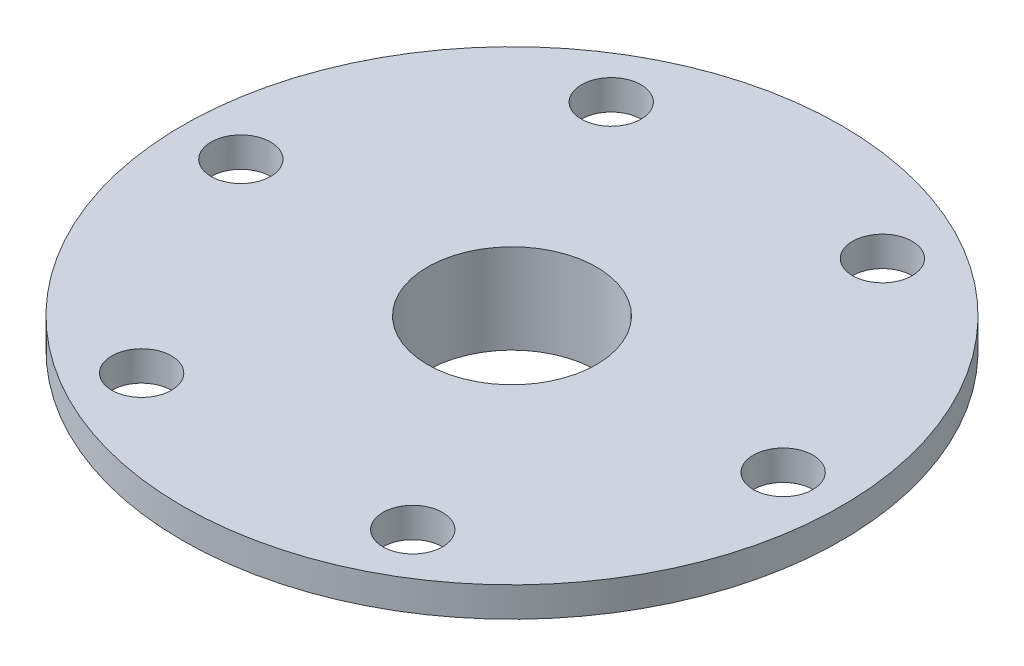
SolidWorks part; units mm, degrees
material "1060 Alloy"
ref_plane "Front Plane" through (0, 0, 0) normal (0, 0, 1) x (1, 0, 0)
ref_plane "Top Plane" through (0, 0, 0) normal (0, 1, 0) x (1, 0, 0)
ref_plane "Right Plane" through (0, 0, 0) normal (1, 0, 0) x (0, 0, -1)
sketch "Sketch4" plane through (0, 0, 0) normal (0, 0, 1) x (1, 0, 0)
  line L0 (0, 27.2792) -> (0, -44.2975) construction
  line L1 (-8.5, 0) -> (-33.1437, 0)
  line L2 (-33.1437, 0) -> (-33.1438, -3)
  line L3 (-33.1438, -3) -> (-12.25, -3)
  line L4 (-12.25, -3) -> (-12.25, -9)
  line L5 (-12.25, -9) -> (-8.5, -9)
  line L6 (-8.5, -9) -> (-8.5, 0)
  line L7 (0, 15) -> (-42.0375, 15) construction
  line L8 (0, 20) -> (-12.5, 20) construction
  line L9 (-12.5, 20) -> (-42.0375, 15) construction
  line L10 (-27.2687, 17.5) -> (-27.2688, 15) construction
  dimension "D2" = 3
  dimension "D3" = 8.5
  dimension "D4" = 12.25
  dimension "D5" = 6
  dimension "D6" = 15
  dimension "D7" = 42.0375
  dimension "D8" = 12.5
  dimension "D9" = 5
  dimension "D1" = 5.875
revolve "Revolve1" add sketch "Sketch4" angle 360 about L0
sketch "Sketch5" plane through (0, 0, 0) normal (0, 1, 0) x (1, 0, 0)
  line L0 (-12.5, 0) -> (-42.0375, 0) construction
  circle A0 centre (0, 0) radius 27.2688 construction
  circle A1 centre (-27.2688, 0) radius 3
  circle A2 centre (-13.6344, 23.6154) radius 3
  circle A3 centre (13.6344, 23.6154) radius 3
  circle A4 centre (27.2688, 0) radius 3
  circle A5 centre (13.6344, -23.6154) radius 3
  circle A6 centre (-13.6344, -23.6154) radius 3
  circle A7 centre (0, 0) radius 12.5 construction
  circle A9 centre (0, 0) radius 42.0375 construction
  point P17 (0, 0)
  point P19 (0, 0)
  dimension "D2" = 6
  dimension "D3" = 25
  dimension "D4" = 84.075
  dimension "D1" = 6
extrude "Cut-Extrude1" cut sketch "Sketch5" against normal through all
equation "\"Stator_OD\"= 68'No Tolerance given"
equation "\"A\"=18.34 'taken off spec sheet for 06808 (A)"
equation "\"Rotor_ID\"= 34'No Tolerance Given"
equation "\"back_bearing_Thickness\"= 8'randomish, thinnest off mcmaster"
equation "\"back_bearing_OD\"= 25'currently non-sense"
equation "\"Stator_Gap\"= 0.0375'+- 0.0125 (From 1.3.3.1 Kollmorgen manual)"
equation "\"Back_mount_hole\"= 1.75'To be tapped to M2 (USE LOCKTITE)"
equation "\"facePlate_Mount_Hole\"= 5.75'To be tapped to M6"
equation "\"final_shaftD\"= 8'NEMA 23 shaft diameter. Should fit with harmonic?"
equation "\"final_shaftL\"= 50'random length. Idk"
equation "\"back_bearing_ID\"= 15'Random number"
equation "\"back_bearing_IDOD\"= 18'Random number, OD of the inner bearing ring"
equation "\"rotor_shaftD\"= \"Rotor_ID\" - (0.0185)*2'+-0.0065 (from manual)"
equation "\"front_bearing_ID\"= 12'random"
equation "\"front_bearing_OD\"= 20'random"
equation "\"front_bearing_IDOD\"= 14'random"
equation "\"front_bearing_Thickness\"= 5'randomish, thinnest off mcmaster"
equation "\"rotor_thickness\"= 2.4'measured off CAD"
equation "\"rotor_height\"= 14.76'+-0.08 taken off spec sheet for 06808 (C)"
equation "\"B\"= 8.2'+-0.35 taken off spec sheet for 06808 (C)"
equation "\"D3@Sketch4\" = \"back_bearing_ID\" / 2 + 1"
equation "\"D4@Sketch4\"=\"back_bearing_OD\"/2-0.25"
equation "\"D3@Sketch5\"=\"back_bearing_OD\""
equation "\"D4@Sketch5\"=\"Stator_OD\"+\"Stator_Gap\"*2+16"
equation "\"D7@Sketch4\"=\"Stator_OD\"/2+\"Stator_Gap\"+8"
equation "\"D8@Sketch4\"=\"back_bearing_OD\"/2"
equation "\"D2@Sketch5\"=\"facePlate_Mount_Hole\"+0.25"
equation "\"D1@Sketch4\"=\"facePlate_Mount_Hole\"/2+3"
